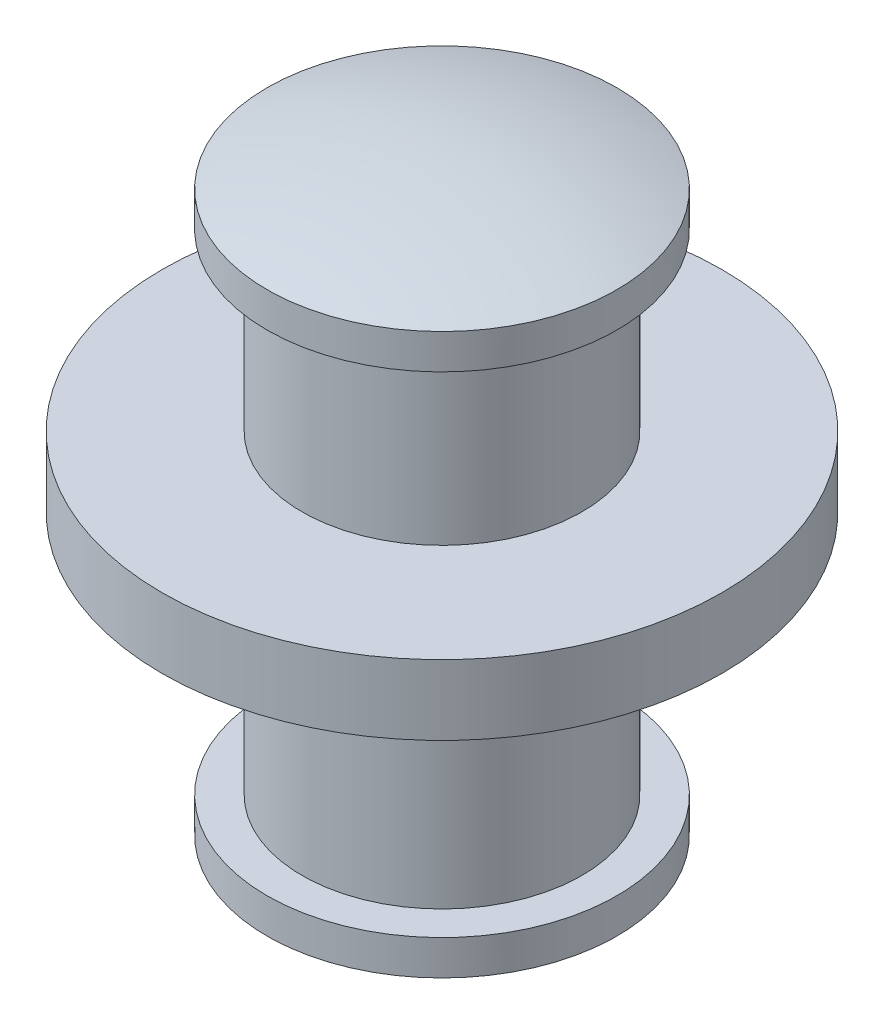
SolidWorks part; units mm, degrees
ref_plane "Face" through (0, 0, 0) normal (0, 0, 1) x (1, 0, 0)
ref_plane "Dessus" through (0, 0, 0) normal (0, 1, 0) x (1, 0, 0)
ref_plane "Droite" through (0, 0, 0) normal (1, 0, 0) x (0, 0, -1)
sketch "Esquisse1" plane through (0, 0, 0) normal (0, 0, 1) x (1, 0, 0)
  line L0 (0, 0) -> (0, 86.769) construction
  line L1 (0, 0) -> (0, -0.6504)
  line L2 (-5, 16) -> (-5, 15)
  line L3 (-5, 15) -> (-4, 15)
  line L4 (-4, 15) -> (-4, 10)
  line L5 (-8, 10) -> (-8, 8)
  line L6 (-8, 8) -> (-4, 8)
  line L7 (-4, 8) -> (-4, 1)
  line L8 (-4, 1) -> (-5, 1)
  line L9 (-5, 1) -> (-5, 0)
  line L11 (0, 0) -> (0, 16)
  line L12 (-8, 10) -> (-4, 10)
  line L13 (0, 16.8035) -> (0, 16)
  arc A0 (-5, 16) -> (0, 16.8035) centre (0, 0.8451) cw
  arc A1 (-5, 0) -> (0, -0.6504) centre (0, 18.8924) ccw
  dimension "D1" = 4
  dimension "D2" = 4
  dimension "D3" = 5
  dimension "D4" = 5
  dimension "D5" = 8
  dimension "D6" = 5
  dimension "D7" = 7
  dimension "D8" = 2
  dimension "D9" = 1
  dimension "D10" = 1
revolve "Base-Révolution" add sketch "Esquisse1" angle 360 about L0
